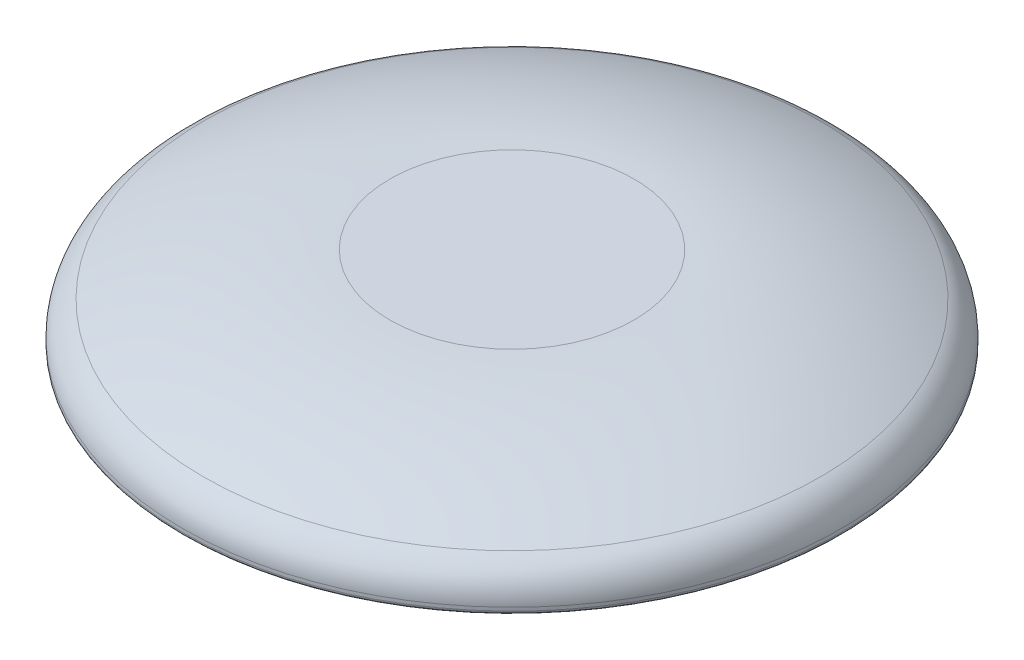
SolidWorks part; units mm, degrees
ref_plane "Front Plane" through (0, 0, 0) normal (0, 0, 1) x (1, 0, 0)
ref_plane "Top Plane" through (0, 0, 0) normal (0, 1, 0) x (1, 0, 0)
ref_plane "Right Plane" through (0, 0, 0) normal (1, 0, 0) x (0, 0, -1)
ref_plane "Plane1" through (0, 0, 0) normal (0, 0, -1) x (-1, 0, 0)
sketch "Sketch1" plane through (0, 0, 0) normal (0, 0, -1) x (-1, 0, 0)
  line L0 (-51.7834, 30.734) -> (0, 30.734)
  line L1 (0, 30.734) -> (0, 35.56)
  line L2 (0, 35.56) -> (-51.7834, 35.56)
  line L3 (-139.7, 3.0042) -> (-139.7, 1.6002)
  line L4 (-138.0998, 0) -> (-136.4742, 0)
  line L5 (-134.874, 1.6002) -> (-134.874, 3.0042)
  line L6 (0, 0) -> (0, 35.56) construction
  arc A0 (-51.7834, 35.56) -> (-130.6942, 17.3958) centre (-51.7834, -144.9281) ccw
  arc A1 (-130.6942, 17.3958) -> (-139.7, 3.0042) centre (-123.698, 3.0042) ccw
  arc A2 (-139.7, 1.6002) -> (-138.0998, 0) centre (-138.0998, 1.6002) ccw
  arc A3 (-136.4742, 0) -> (-134.874, 1.6002) centre (-136.4742, 1.6002) ccw
  arc A4 (-134.874, 3.0042) -> (-128.5842, 13.0554) centre (-123.698, 3.0042) cw
  arc A5 (-128.5842, 13.0554) -> (-51.7834, 30.734) centre (-51.7834, -144.9281) cw
revolve "Revolve1" add sketch "Sketch1" angle 360 about L6
